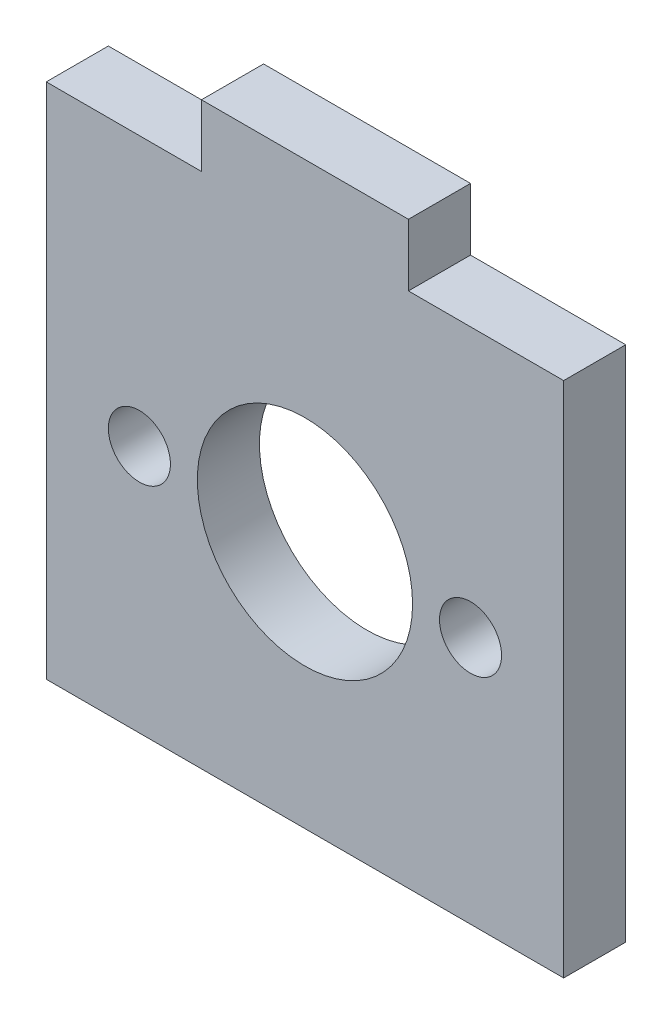
SolidWorks part; units mm, degrees
ref_plane "Front Plane" through (0, 0, 0) normal (0, 0, 1) x (1, 0, 0)
ref_plane "Top Plane" through (0, 0, 0) normal (0, 1, 0) x (1, 0, 0)
ref_plane "Right Plane" through (0, 0, 0) normal (1, 0, 0) x (0, 0, -1)
sketch "Sketch1" plane through (0, 0, 0) normal (0, 0, 1) x (1, 0, 0)
  line L0 (-12.5, 13) -> (-12.5, -12)
  line L1 (-12.5, -12) -> (12.5, -12)
  line L2 (12.5, -12) -> (12.5, 13)
  line L3 (12.5, 13) -> (5, 13)
  line L4 (-5, 13) -> (-5, 16)
  line L5 (-5, 16) -> (5, 16)
  line L6 (5, 16) -> (5, 13)
  line L7 (-5, 13) -> (-12.5, 13)
  circle A0 centre (0, 0) radius 5.2
  circle A1 centre (-8, 0) radius 1.5
  circle A2 centre (8, 0) radius 1.5
  dimension "D1" = 3
  dimension "D2" = 10.4
  dimension "D3" = 8
  dimension "D4" = 8
  dimension "D5" = 13
  dimension "D6" = 12.5
  dimension "D7" = 12.5
  dimension "D8" = 25
  dimension "D9" = 10
  dimension "D10" = 7.5
  dimension "D11" = 3
extrude "Boss-Extrude1" add sketch "Sketch1" along normal blind 3
